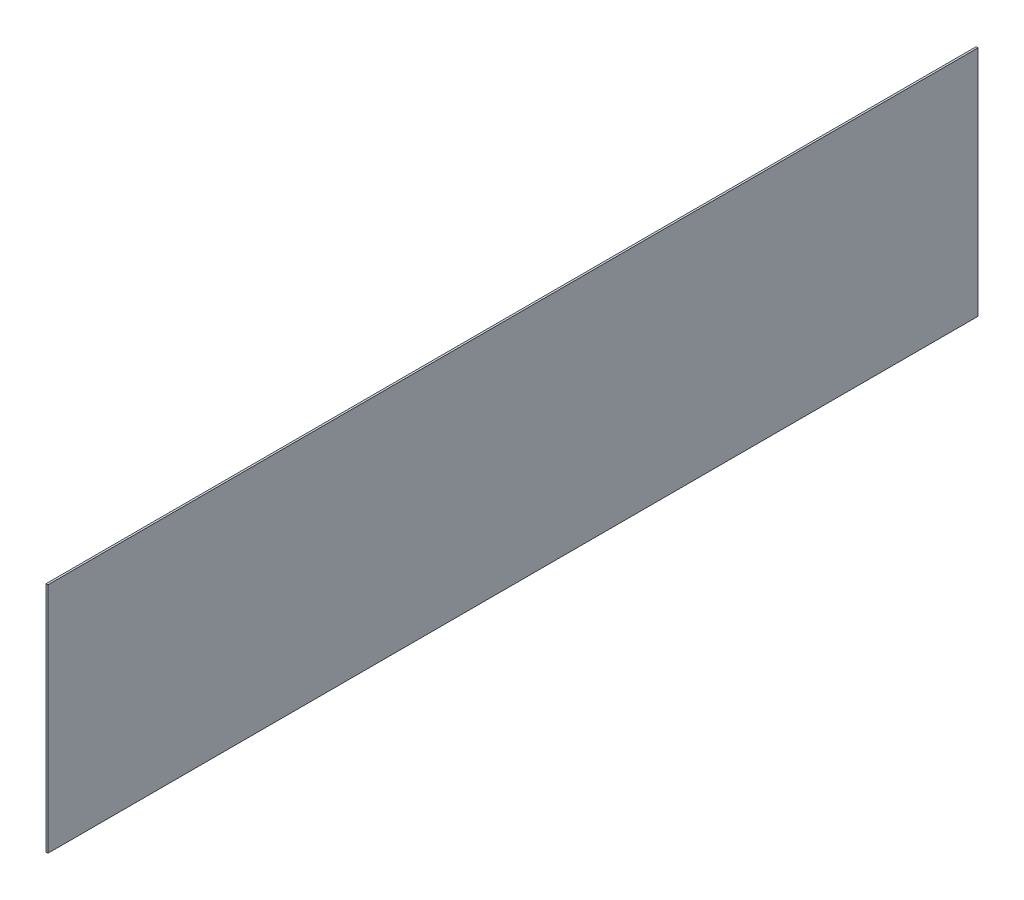
SolidWorks part; units mm, degrees
material "5052-H32"
ref_plane "Front Plane" through (0, 0, 0) normal (0, 0, 1) x (1, 0, 0)
ref_plane "Top Plane" through (0, 0, 0) normal (0, 1, 0) x (1, 0, 0)
ref_plane "Right Plane" through (0, 0, 0) normal (1, 0, 0) x (0, 0, -1)
sketch "Sketch1" plane through (0, 0, 0) normal (1, 0, 0) x (0, 0, -1)
  line L1 (-152.4, 76.2) -> (152.4, 76.2)
  line L2 (-152.4, 76.2) -> (-152.4, 0)
  line L3 (-152.4, 0) -> (152.4, 0)
  line L4 (152.4, 76.2) -> (152.4, 0)
  dimension "D1" = 304.8
  dimension "D2" = 76.2
extrude "Boss-Extrude1" add sketch "Sketch1" along normal mid plane 0.635
